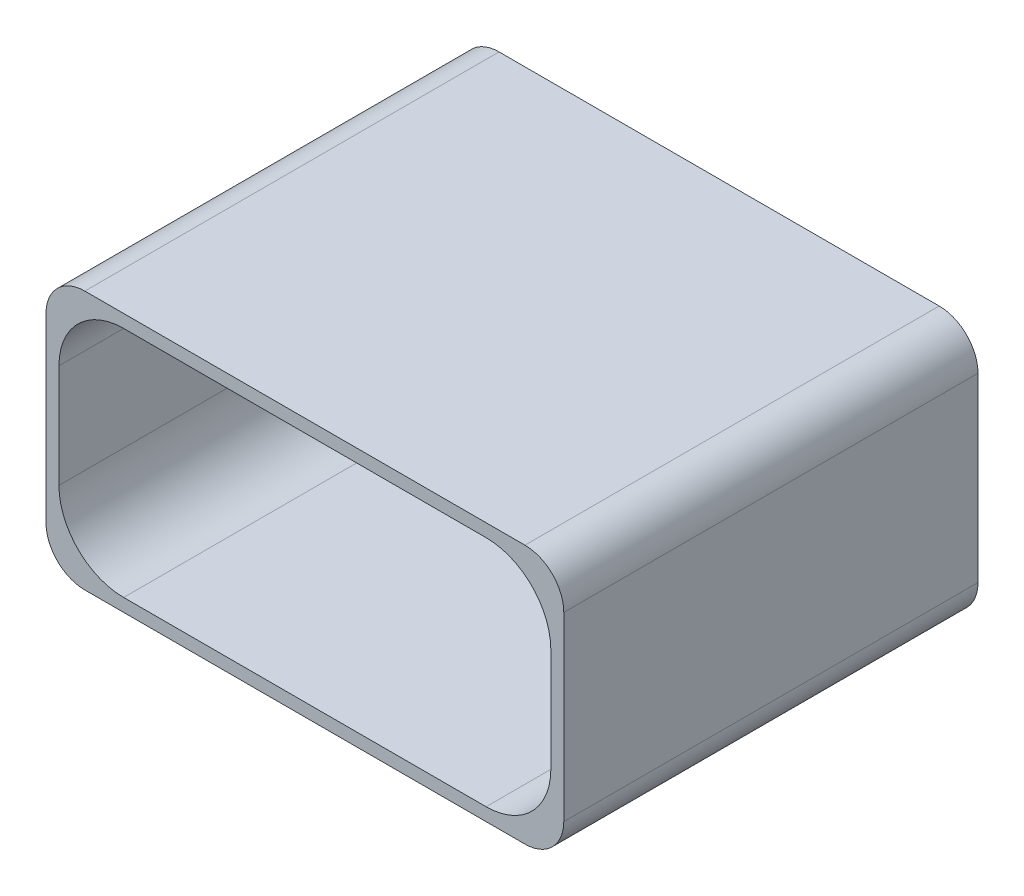
SolidWorks part; units mm, degrees
ref_plane "Front Plane" through (0, 0, 0) normal (0, 0, 1) x (1, 0, 0)
ref_plane "Top Plane" through (0, 0, 0) normal (0, 1, 0) x (1, 0, 0)
ref_plane "Right Plane" through (0, 0, 0) normal (1, 0, 0) x (0, 0, -1)
sketch "Sketch1" plane through (0, 0, 0) normal (0, 0, 1) x (1, 0, 0)
  line L0 (0, 0) -> (200, 0)
  line L1 (200, 0) -> (200, 100)
  line L2 (200, 100) -> (0, 100)
  line L3 (0, 100) -> (0, 0)
  dimension "D1" = 200
  dimension "D2" = 100
extrude "Boss-Extrude1" add sketch "Sketch1" along normal blind 10
sketch "Sketch2" plane through (0, 0, 10) normal (0, 0, 1) x (1, 0, 0)
  line L0 (15, 100) -> (185, 100)
  line L1 (200, 85) -> (200, 15)
  line L2 (185, 0) -> (15, 0)
  line L3 (0, 15) -> (0, 85)
  line L4 (0, 85) -> (0, 100)
  line L5 (0, 100) -> (200, 100)
  line L6 (200, 100) -> (200, 0)
  line L7 (200, 0) -> (0, 0)
  line L8 (0, 0) -> (0, 100)
  arc A0 (15, 0) -> (0, 15) centre (15, 15) cw
  arc A1 (200, 15) -> (185, 0) centre (185, 15) cw
  arc A2 (185, 100) -> (200, 85) centre (185, 85) cw
  arc A3 (15, 100) -> (0, 85) centre (15, 85) ccw
  point P10 (0, 0)
  point P13 (200, 0)
  point P16 (200, 100)
  point P19 (0, 100)
  line M9 (0, 100) -> (0, 0)
  line M10 (0, 0) -> (200, 0)
  line M11 (200, 0) -> (200, 100)
  line M12 (200, 100) -> (0, 100)
  dimension "D1" = 15
extrude "Cut-Extrude1" cut sketch "Sketch2" against normal blind 10 contours A3 M12 M9 | A2 M12 M11 | A1 M11 M10 | A0 M10 M9
sketch "Sketch3" plane through (0, 0, 10) normal (0, 0, 1) x (1, 0, 0)
  line L0 (100, 100) -> (185, 100)
  line L1 (185, 100) -> (15, 100) construction
  line L2 (100, 100) -> (15, 100)
  line L3 (200, 85) -> (200, 15)
  line L4 (185, 0) -> (15, 0)
  line L5 (0, 15) -> (0, 85)
  line L6 (30, 85) -> (170, 85)
  line L7 (185, 70) -> (185, 30)
  line L8 (170, 15) -> (30, 15)
  line L9 (15, 30) -> (15, 70)
  line L10 (30, 95) -> (170, 95)
  line L11 (195, 70) -> (195, 30)
  line L12 (170, 5) -> (30, 5)
  line L13 (5, 30) -> (5, 70)
  arc A0 (15, 0) -> (0, 15) centre (15, 15) cw
  arc A1 (200, 15) -> (185, 0) centre (185, 15) cw
  arc A2 (185, 100) -> (200, 85) centre (185, 85) cw
  arc A3 (15, 100) -> (0, 85) centre (15, 85) ccw
  arc A4 (30, 15) -> (15, 30) centre (30, 30) cw
  arc A5 (185, 30) -> (170, 15) centre (170, 30) cw
  arc A6 (170, 85) -> (185, 70) centre (170, 70) cw
  arc A7 (30, 85) -> (15, 70) centre (30, 70) ccw
  arc A8 (170, 95) -> (195, 70) centre (170, 70) cw
  arc A9 (195, 30) -> (170, 5) centre (170, 30) cw
  arc A10 (30, 5) -> (5, 30) centre (30, 30) cw
  arc A11 (30, 95) -> (5, 70) centre (30, 70) ccw
  point P11 (0, 0)
  point P14 (200, 0)
  point P17 (200, 100)
  point P20 (0, 100)
  dimension "D5" = 15
  dimension "D6" = 15
  dimension "D1" = 100
  dimension "D2" = 100
  dimension "D3" = 100
  dimension "D4" = 200
  dimension "D7" = 10
extrude "Boss-Extrude2" add sketch "Sketch3" along normal blind 150 contours L6 A7 L9 A4 L8 A5 L7 A6 | L10 A11 L13 A10 L12 A9 L11 A8 A7 L6 A6 L7 A5 L8 A4 L9 | L0 A2 L3 A1 L4 A0 L5 A3 L2
sketch "Sketch4" plane through (0, 0, 10) normal (0, 0, 1) x (1, 0, 0)
  line L0 (100, 95) -> (100, 5)
  line L1 (30, 95) -> (170, 95) construction
  line L2 (170, 5) -> (30, 5) construction
  line L3 (100, 50) -> (135, 50)
  line L4 (100, 50) -> (65, 50)
  line L5 (65, 50) -> (65, 50.5)
  line L6 (65, 50) -> (65, 49.5)
  line L7 (65, 50.5) -> (66, 50.5)
  line L8 (65, 49.5) -> (66, 49.5)
  line L9 (66, 50.5) -> (66, 60.5)
  line L10 (66, 49.5) -> (66, 39.5)
  line L11 (66, 60.5) -> (56, 60.5)
  line L12 (66, 39.5) -> (56, 39.5)
  line L13 (56, 60.5) -> (56, 39.5)
  line L14 (135, 50) -> (135, 50.5)
  line L15 (135, 50) -> (135, 49.5)
  line L16 (135, 50.5) -> (134, 50.5)
  line L17 (135, 49.5) -> (134, 49.5)
  line L18 (134, 50.5) -> (134, 60.5)
  line L19 (134, 49.5) -> (134, 39.5)
  line L20 (134, 60.5) -> (144, 60.5)
  line L21 (144, 60.5) -> (144, 39.5)
  line L22 (144, 39.5) -> (134, 39.5)
  dimension "D1" = 35
  dimension "D2" = 35
  dimension "D3" = 0.5
  dimension "D4" = 0.5
  dimension "D5" = 1
  dimension "D6" = 1
  dimension "D7" = 10
  dimension "D8" = 10
  dimension "D9" = 10
  dimension "D10" = 10
  dimension "D11" = 0.5
  dimension "D12" = 0.5
  dimension "D13" = 1
  dimension "D14" = 1
  dimension "D15" = 10
  dimension "D16" = 10
  dimension "D17" = 10
extrude "Boss-Extrude3" add sketch "Sketch4" along normal blind 80 contours L11 L13 L12 L10 L8 L6 L5 L7 L9 | L22 L21 L20 L18 L16 L14 L15 L17 L19
